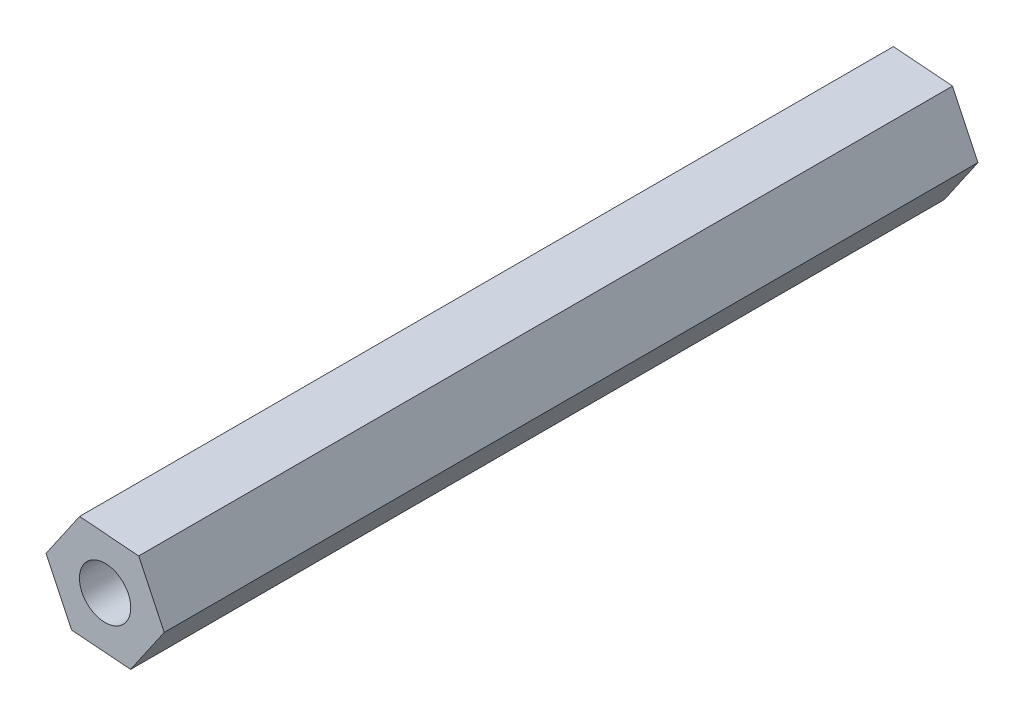
SolidWorks part; units mm, degrees
ref_plane "Plan de face" through (0, 0, 0) normal (0, 0, 1) x (1, 0, 0)
ref_plane "Plan de dessus" through (0, 0, 0) normal (0, 1, 0) x (1, 0, 0)
ref_plane "Plan de droite" through (0, 0, 0) normal (1, 0, 0) x (0, 0, -1)
sketch "Esquisse1" plane through (0, 0, 0) normal (0, 0, 1) x (1, 0, 0)
  line L1 (-2.0365, 4.2739) -> (-4.7195, 0.3732)
  line L2 (-4.7195, 0.3732) -> (-2.683, -3.9006)
  line L3 (-2.683, -3.9006) -> (2.0365, -4.2739)
  line L4 (2.0365, -4.2739) -> (4.7195, -0.3732)
  line L5 (4.7195, -0.3732) -> (2.683, 3.9006)
  line L6 (2.683, 3.9006) -> (-2.0365, 4.2739)
  circle A0 centre (0, 0) radius 2.05
  circle A1 centre (0, 0) radius 4.1 construction
  dimension "D1" = 4.1
  dimension "D2" = 4.1
extrude "Boss.-Extru.1" add sketch "Esquisse1" along normal blind 65 contours L5 L6 L1 L2 L3 L4
